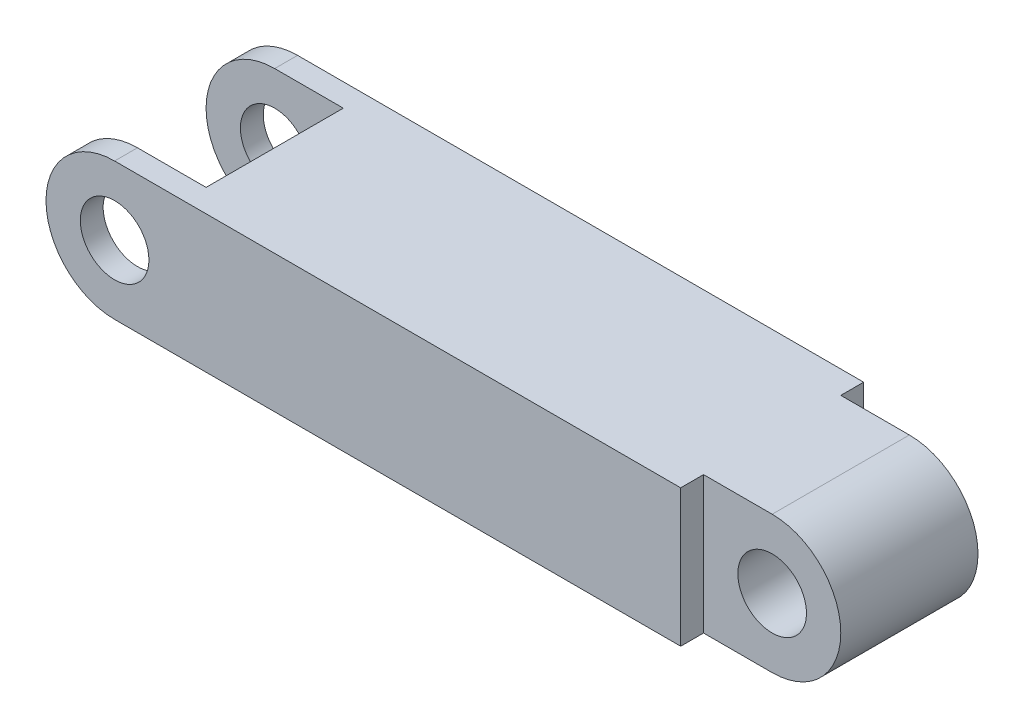
SolidWorks part; units mm, degrees
ref_plane "Front Plane" through (0, 0, 0) normal (0, 0, 1) x (1, 0, 0)
ref_plane "Top Plane" through (0, 0, 0) normal (0, 1, 0) x (1, 0, 0)
ref_plane "Right Plane" through (0, 0, 0) normal (1, 0, 0) x (0, 0, -1)
sketch "Sketch1" plane through (0, 0, 0) normal (0, 0, 1) x (1, 0, 0)
  line L0 (0, 0) -> (138.7615, 0) construction
  line L1 (0, 15) -> (138.7615, 15)
  line L2 (0, -15) -> (138.7615, -15)
  arc A0 (0, 15) -> (0, -15) centre (0, 0) ccw
  arc A1 (138.7615, -15) -> (138.7615, 15) centre (138.7615, 0) ccw
  circle A2 centre (0, 0) radius 7.5
  circle A3 centre (138.7615, 0) radius 7.5
  point P3 (69.3807, 0)
  point P12 (138.7615, 0)
  dimension "D1" = 15
  dimension "D2" = 15
  dimension "D3" = 30
extrude "Boss-Extrude1" add sketch "Sketch1" along normal blind 40
sketch "Sketch2" plane through (0, 15, 0) normal (0, 1, 0) x (1, 0, 0)
  line L0 (-15, 0) -> (-15, -40) construction
  line L1 (15, -5) -> (-15, -5)
  line L2 (15, -5) -> (15, -35)
  line L3 (15, -35) -> (-15, -35)
  line L4 (-15, -5) -> (-15, -35)
  line L6 (0, -40) -> (0, 0) construction
  line L7 (153.7615, 0) -> (123.7615, 0)
  line L8 (153.7615, 0) -> (153.7615, -5)
  line L9 (153.7615, -5) -> (123.7615, -5)
  line L10 (123.7615, 0) -> (123.7615, -5)
  line L11 (153.7615, -40) -> (123.7615, -40)
  line L12 (153.7615, -40) -> (153.7615, -35)
  line L13 (153.7615, -35) -> (123.7615, -35)
  line L14 (123.7615, -40) -> (123.7615, -35)
  point P7 (-15, -20)
  point P10 (0, -20)
  dimension "D1" = 30
  dimension "D2" = 30
extrude "Cut-Extrude1" cut sketch "Sketch2" against normal through all
